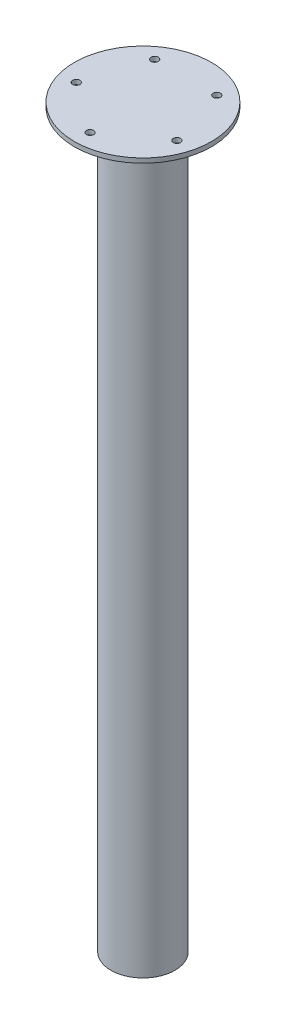
SolidWorks part; units mm, degrees
material "Alloy Steel"
ref_plane "Front" through (0, 0, 0) normal (0, 0, 1) x (1, 0, 0)
ref_plane "Top" through (0, 0, 0) normal (0, 1, 0) x (1, 0, 0)
ref_plane "Right" through (0, 0, 0) normal (1, 0, 0) x (0, 0, -1)
sketch "Sketch1" plane through (0, 0, 0) normal (0, 1, 0) x (1, 0, 0)
  circle A0 centre (0, 0) radius 35
  dimension "D1" = 70
extrude "Boss-Extrude1" add sketch "Sketch1" along normal blind 800
sketch "Sketch2" plane through (0, 800, 0) normal (0, 1, 0) x (1, 0, 0)
  circle A0 centre (0, 0) radius 75
  dimension "D1" = 150
extrude "Boss-Extrude2" add sketch "Sketch2" along normal blind 5
fillet "Fillet1" radius 10 1 edges at (0, 800, 35)
hole_wizard "Ø8.0 (8) Diameter Hole1" positions "Sketch4" profile "Sketch3" hole size "Ø8.0" standard "ISO" end condition up to next
sketch "Sketch4" plane through (0, 805, 0) normal (0, 1, 0) x (1, 0, 0)
  point P0 (0, -57.858)
sketch "Sketch3" plane through (0, 805, 57.858) normal (1, 0, 0) x (0, 0, 1)
  line L0 (0, 0) -> (0, 5)
  line L1 (0, 5) -> (4, 5)
  line L2 (4, 5) -> (4, 0)
  line L5 (4, 0) -> (0, 0)
  line L11 (0, -6.35) -> (0, 107.95) construction
  dimension "Thru Hole Dia." = 8
  dimension "Thru Hole Depth" = 5
pattern_circular "CirPattern1" count 5 over 360 about axis through (0, 0, 0) along (0, 1, 0) of "Ø8.0 (8) Diameter Hole1"
sketch "Sketch6" plane through (0, 0, 0) normal (0, -1, 0) x (1, 0, 0)
  circle A0 centre (0, 0) radius 35 construction
  circle A1 centre (0, 0) radius 35
